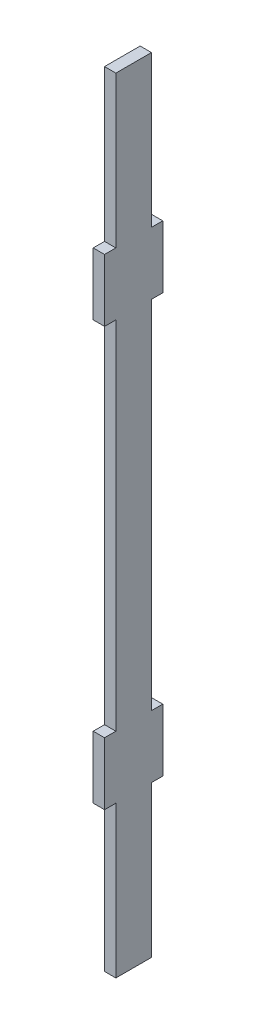
SolidWorks part; units mm, degrees
ref_plane "Front Plane" through (0, 0, 0) normal (0, 0, 1) x (1, 0, 0)
ref_plane "Top Plane" through (0, 0, 0) normal (0, 1, 0) x (1, 0, 0)
ref_plane "Right Plane" through (0, 0, 0) normal (1, 0, 0) x (0, 0, -1)
sketch "Sketch3" plane through (0, 0, 0) normal (1, 0, 0) x (0, 0, -1)
  line L0 (0, 0) -> (-17.0044, 0) construction
  line L1 (-5, -220) -> (5, -220)
  line L3 (-15, 220) -> (5, 220)
  line L4 (5, -220) -> (5, -135)
  line L5 (-5, -220) -> (5, 220) construction
  line L6 (-5, 220) -> (5, -220) construction
  line L7 (0, 0) -> (0, 72.0347) construction
  line L8 (5, 100) -> (11.35, 100)
  line L9 (11.35, 100) -> (11.35, 135)
  line L10 (11.35, 135) -> (5, 135)
  line L11 (5, 135) -> (5, 220)
  line L12 (-5, 220) -> (-5, -220) construction
  line L13 (11.35, -135) -> (5, -135)
  line L14 (11.35, -100) -> (11.35, -135)
  line L15 (5, -100) -> (11.35, -100)
  line L16 (5, -100) -> (5, 100)
  line L17 (-21.35, 100) -> (-21.35, 135)
  line L18 (-15, 100) -> (-21.35, 100)
  line L19 (-21.35, 135) -> (-15, 135)
  line L20 (-15, 135) -> (-15, 220)
  line L21 (-15, -100) -> (-15, 100)
  line L22 (-15, -100) -> (-21.35, -100)
  line L23 (-21.35, -100) -> (-21.35, -135)
  line L24 (-21.35, -135) -> (-15, -135)
  line L25 (-15, -220) -> (-15, -135)
  line L26 (-5, -220) -> (-15, -220)
  point P0 (0, 0)
  point P6 (0, -220)
  dimension "D1" = 10
  dimension "D2" = 440
  dimension "D3" = 35
  dimension "D4" = 135
  dimension "D5" = 6.35
extrude "Boss-Extrude1" add sketch "Sketch3" along normal blind 6.35
